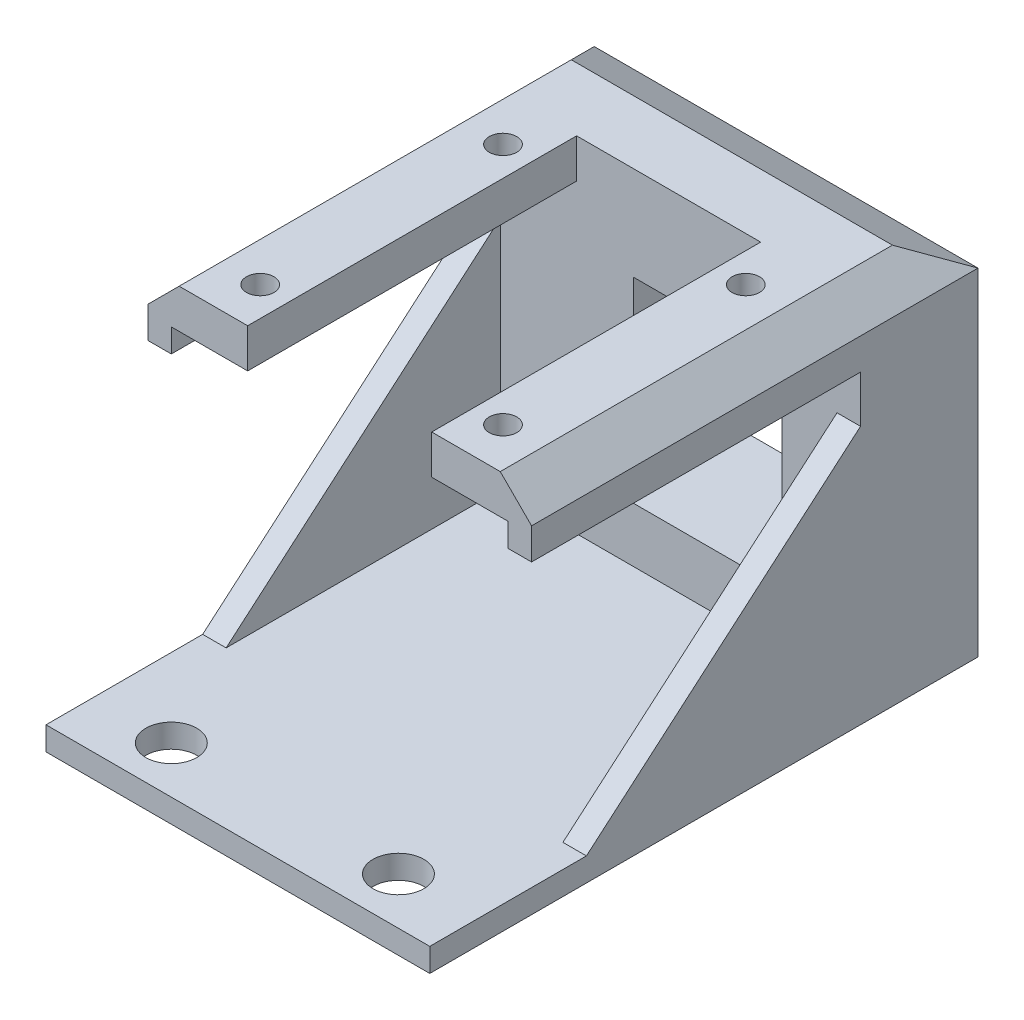
SolidWorks part; units mm, degrees
ref_plane "Front Plane" through (0, 0, 0) normal (0, 0, 1) x (1, 0, 0)
ref_plane "Top Plane" through (0, 0, 0) normal (0, 1, 0) x (1, 0, 0)
ref_plane "Right Plane" through (0, 0, 0) normal (1, 0, 0) x (0, 0, -1)
sketch "Sketch1" plane through (0, 0, 0) normal (0, 0, 1) x (1, 0, 0)
  line L1 (-26.9022, 22.8668) -> (22.0978, 22.8668)
  line L2 (-26.9022, 22.8668) -> (-26.9022, -24.1332)
  line L3 (-26.9022, -24.1332) -> (22.0978, -24.1332)
  line L4 (22.0978, 22.8668) -> (22.0978, -24.1332)
  dimension "D1" = 49
  dimension "D2" = 47
extrude "Boss-Extrude1" add sketch "Sketch1" along normal blind 15
sketch "Sketch2" plane through (0, 0, 15) normal (0, 0, 1) x (1, 0, 0)
  line L0 (22.0978, -24.1332) -> (22.0978, 22.8668) construction
  line L1 (-26.9022, -24.1332) -> (22.0978, -24.1332)
  line L2 (-26.9022, -24.1332) -> (-26.9022, -21.1332)
  line L3 (-26.9022, -21.1332) -> (22.0978, -21.1332)
  line L4 (22.0978, -24.1332) -> (22.0978, -21.1332)
  dimension "D1" = 3
extrude "Boss-Extrude2" add sketch "Sketch2" along normal blind 55
sketch "Sketch4" plane through (-26.9022, 0, 0) normal (-1, 0, 0) x (0, 0, 1)
  line L0 (15, -21.1332) -> (15, 8.8668)
  line L1 (15, 22.8668) -> (15, -21.1332) construction
  line L2 (15, 8.8668) -> (50, -21.1332)
  line L3 (70, -21.1332) -> (15, -21.1332) construction
  line L4 (50, -21.1332) -> (15, -21.1332)
  dimension "D1" = 30
  dimension "D2" = 35
extrude "Boss-Extrude3" add sketch "Sketch4" against normal blind 3
sketch "Sketch5" plane through (22.0978, 0, 0) normal (1, 0, 0) x (0, 0, -1)
  line L0 (-15, -21.1332) -> (-15, 8.8668)
  line L1 (-15, 8.8668) -> (-50, -21.1332)
  line L2 (-50, -21.1332) -> (-15, -21.1332)
extrude "Boss-Extrude4" add sketch "Sketch5" against normal blind 3
sketch "Sketch7" plane through (0, 0, 0) normal (0, 0, -1) x (-1, 0, 0)
  line L0 (26.9022, -24.1332) -> (-22.0978, -24.1332) construction
  line L1 (26.9022, 22.8668) -> (26.9022, -24.1332) construction
  circle A0 centre (16.9022, 5.8668) radius 4.2
  dimension "D1" = 30
  dimension "D2" = 10
extrude "Cut-Extrude1" cut sketch "Sketch7" against normal blind 9 contours A0
sketch "Sketch8" plane through (0, 0, 15) normal (0, 0, 1) x (1, 0, 0)
  line L0 (-2.4022, 22.8668) -> (-2.4022, -24.1332) construction
  line L1 (22.0978, 22.8668) -> (9.3478, 22.8668)
  line L2 (22.0978, 22.8668) -> (22.0978, 18.7847)
  line L3 (19.0978, 17.8668) -> (9.3478, 17.8668)
  line L4 (9.3478, 22.8668) -> (9.3478, 17.8668)
  line L5 (22.0978, 22.8668) -> (-26.9022, 22.8668) construction
  line L6 (-26.9022, -24.1332) -> (22.0978, -24.1332) construction
  line L7 (19.0978, 17.8668) -> (19.0978, 14.8668)
  line L8 (19.0978, 14.8668) -> (22.0978, 14.8668)
  line L9 (22.0978, 8.8668) -> (22.0978, 22.8668) construction
  line L10 (22.0978, 14.8668) -> (22.0978, 18.7847)
  line L11 (-26.9022, 14.8668) -> (-26.9022, 18.7847)
  line L12 (-23.9022, 14.8668) -> (-26.9022, 14.8668)
  line L13 (-23.9022, 17.8668) -> (-23.9022, 14.8668)
  line L14 (-14.1522, 22.8668) -> (-14.1522, 17.8668)
  line L15 (-23.9022, 17.8668) -> (-14.1522, 17.8668)
  line L16 (-26.9022, 22.8668) -> (-26.9022, 18.7847)
  line L17 (-26.9022, 22.8668) -> (-14.1522, 22.8668)
  dimension "D1" = 5
  dimension "D2" = 3
  dimension "D3" = 3
  dimension "D4" = 9.75
extrude "Boss-Extrude5" add sketch "Sketch8" along normal blind 42
sketch "Sketch9" plane through (0, 22.8668, 0) normal (0, 1, 0) x (1, 0, 0)
  circle A0 centre (13.0978, -51.65) radius 1.75
  circle A1 centre (13.0978, -20.65) radius 1.75
  circle A2 centre (-17.9022, -20.65) radius 1.75
  circle A3 centre (-17.9022, -51.65) radius 1.75
extrude "Cut-Extrude2" cut sketch "Sketch9" against normal up to surface (5 mm away) up to face at (-19.0272, 17.8668, 36)
chamfer "Chamfer1" distance 4 angle 45 2 edges at (22.0978, 22.8668, 28.5) (-26.9022, 22.8668, 28.5)
chamfer "Chamfer2" distance 4 angle 60 1 edges at (-2.4022, 22.8668, 0)
sketch "Sketch10" plane through (0, 0, 0) normal (0, 0, -1) x (-1, 0, 0)
  line L0 (-22.0978, -24.1332) -> (-22.0978, 18.8668) construction
  line L1 (-12.0978, 10.8668) -> (6.9022, 10.8668)
  line L2 (-12.0978, 10.8668) -> (-12.0978, -14.1332)
  line L3 (-12.0978, -14.1332) -> (6.9022, -14.1332)
  line L4 (6.9022, 10.8668) -> (6.9022, -4.1332)
  line L5 (26.9022, -24.1332) -> (-22.0978, -24.1332) construction
  line L6 (26.9022, 18.8668) -> (-22.0978, 18.8668) construction
  line L7 (26.9022, 18.8668) -> (26.9022, -24.1332) construction
  line L9 (6.9022, -14.1332) -> (16.9022, -14.1332)
  line L11 (6.9022, -4.1332) -> (16.9022, -4.1332)
  line L12 (16.9022, -14.1332) -> (16.9022, -4.1332)
  dimension "D1" = 10
  dimension "D2" = 10
  dimension "D3" = 8
  dimension "D4" = 20
  dimension "D5" = 10
  dimension "D6" = 10
extrude "Cut-Extrude3" cut sketch "Sketch10" against normal up to surface (15 mm away) up to face at (-2.4022, 10.6168, 15)
sketch "Sketch11" plane through (0, -21.1332, 0) normal (0, 1, 0) x (1, 0, 0)
  line L0 (22.0978, -70) -> (22.0978, -50) construction
  line L1 (-26.9022, -70) -> (-26.9022, -50) construction
  line L2 (22.0978, -70) -> (-26.9022, -70) construction
  circle A0 centre (12.0978, -64) radius 3.25
  circle A1 centre (-16.9022, -64) radius 3.25
  dimension "D1" = 10
  dimension "D2" = 10
  dimension "D3" = 6
extrude "Cut-Extrude4" cut sketch "Sketch11" against normal up to surface (3 mm away) up to face at (-2.4022, -24.1332, 35)
